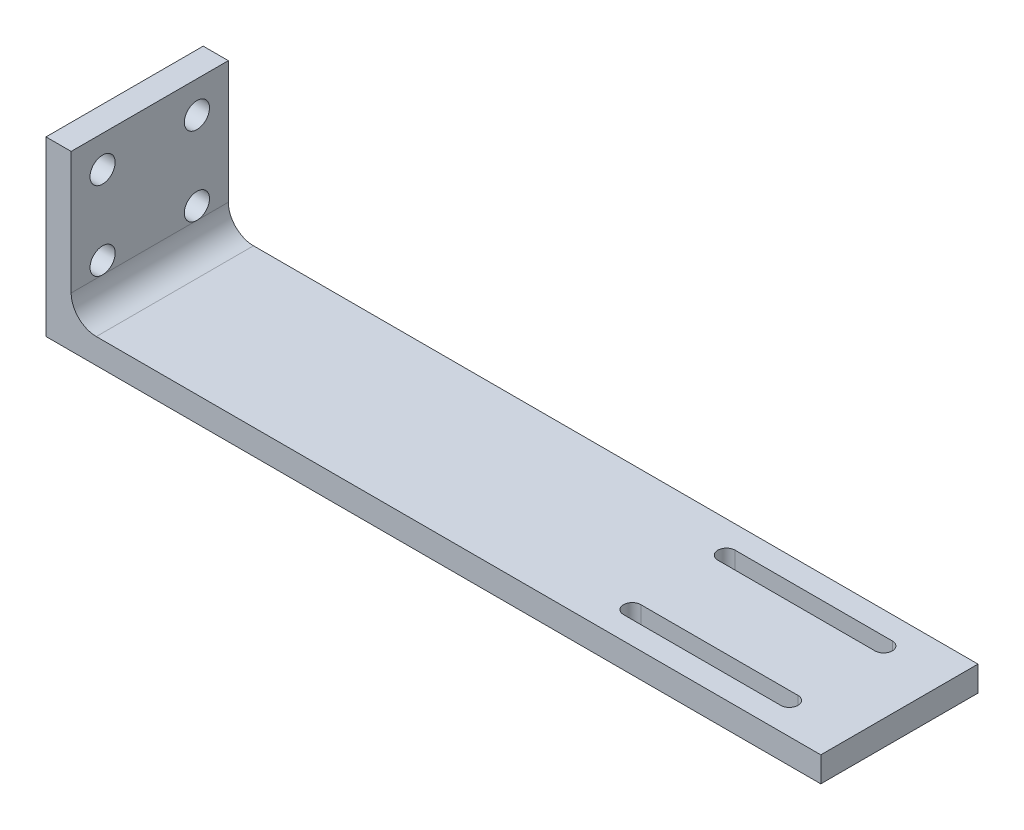
SolidWorks part; units mm, degrees
ref_plane "前视基准面" through (0, 0, 0) normal (0, 0, 1) x (1, 0, 0)
ref_plane "上视基准面" through (0, 0, 0) normal (0, 1, 0) x (1, 0, 0)
ref_plane "右视基准面" through (0, 0, 0) normal (1, 0, 0) x (0, 0, -1)
sketch "草图1" plane through (0, 0, 0) normal (1, 0, 0) x (0, 0, -1)
  line L1 (-25, 35) -> (25, 35)
  line L2 (-25, 35) -> (-25, -20)
  line L3 (-25, -20) -> (25, -20)
  line L4 (25, 35) -> (25, -20)
  dimension "D1" = 50
  dimension "D2" = 55
  dimension "D3" = 25
  dimension "D4" = 20
extrude "凸台-拉伸1" add sketch "草图1" along normal blind 8
sketch "草图2" plane through (0, -20, 0) normal (0, -1, 0) x (1, 0, 0)
  line L0 (0, 25) -> (8, 25)
  line L1 (8, 25) -> (246.45, 25)
  line L2 (0, -25) -> (8, -25)
  line L3 (8, -25) -> (246.45, -25)
  line L4 (0, 25) -> (0, -25)
  line L5 (246.45, 25) -> (246.45, -25)
  dimension "D1" = 246.45
extrude "凸台-拉伸2" add sketch "草图2" against normal blind 8
fillet "圆角1" radius 8 1 edges at (8, -12, 0)
sketch "草图3" plane through (0, -20, 0) normal (0, -1, 0) x (1, 0, 0)
  line L0 (246.45, -25) -> (0, -25) construction
  line L2 (246.45, -25) -> (246.45, 25) construction
  line L3 (226.45, -12.25) -> (120, -12.25)
  line L4 (226.45, -17.75) -> (120, -17.75)
  line L5 (226.45, 12.25) -> (120, 12.25)
  line L6 (226.45, 17.75) -> (120, 17.75)
  circle A0 centre (226.45, -15) radius 2.75
  circle A1 centre (226.45, 15) radius 2.75
  circle A2 centre (176.45, -15) radius 2.75
  circle A3 centre (176.45, 15) radius 2.75
  dimension "D1" = 5.5
  dimension "D2" = 5.5
  dimension "D5" = 5.5
  dimension "D6" = 5.5
  dimension "D8" = 30
  dimension "D9" = 50
  dimension "D10" = 20
  dimension "D3" = 30
  dimension "D4" = 10
extrude "切除-拉伸1" cut sketch "草图3" against normal blind 8 contours A2 L4 A0 L3 | A0 | A2 | A3 L5 A1 L6 | A1
sketch "草图4" plane through (0, 0, 0) normal (-1, 0, 0) x (0, 0, 1)
  line L4 (-25, -20) -> (25, -20)
  line L5 (25, -20) -> (25, 35)
  line L6 (25, 35) -> (-25, 35)
  line L7 (-25, 35) -> (-25, -20)
  line L8 (-25, -20) -> (25, -20)
  line L9 (25, -20) -> (25, 35)
  line L10 (25, 35) -> (-25, 35)
  line L11 (-25, 35) -> (-25, -20)
  circle A0 centre (-15, 25) radius 4
  circle A1 centre (15, 25) radius 4
  circle A2 centre (-15, 0) radius 4
  circle A3 centre (15, 0) radius 4
  dimension "D1" = 8
  dimension "D2" = 8
  dimension "D3" = 8
  dimension "D4" = 8
  dimension "D6" = 30
  dimension "D8" = 10
  dimension "D5" = 30
  dimension "D9" = 25
  dimension "D10" = 10
  dimension "D7" = 0
extrude "切除-拉伸2" cut sketch "草图4" against normal blind 8 contours A0 | A2 | A1 | A3
